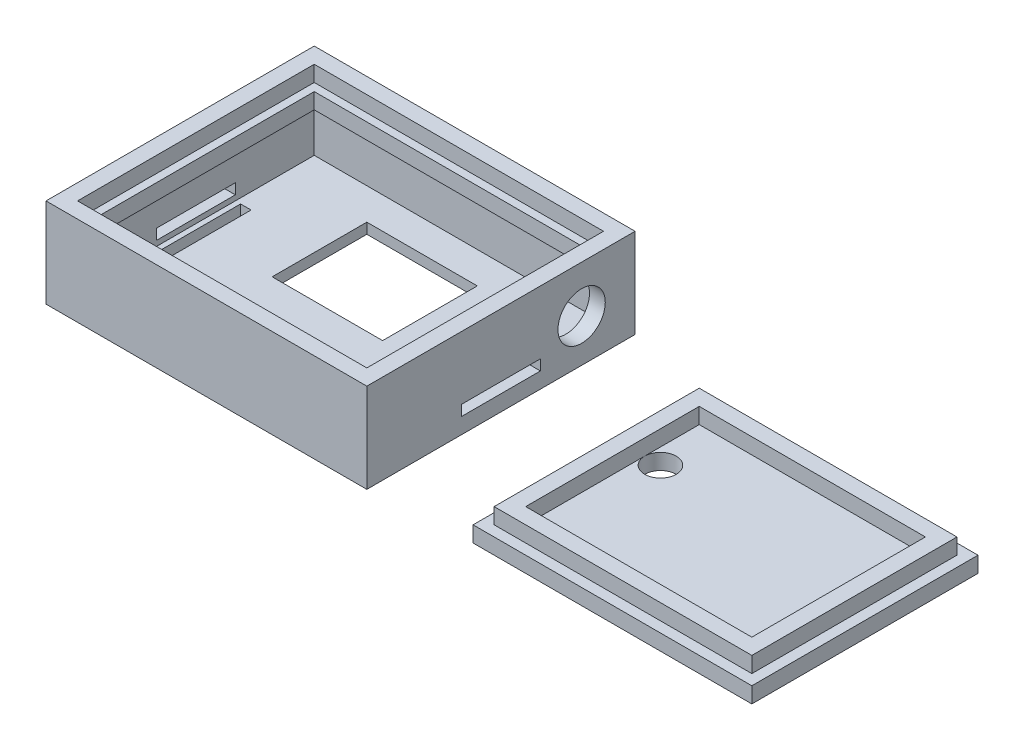
SolidWorks part; units mm, degrees
ref_plane "Front Plane" through (0, 0, 0) normal (0, 0, 1) x (1, 0, 0)
ref_plane "Top Plane" through (0, 0, 0) normal (0, 1, 0) x (1, 0, 0)
ref_plane "Right Plane" through (0, 0, 0) normal (1, 0, 0) x (0, 0, -1)
sketch "Sketch1" plane through (0, 0, 0) normal (0, 1, 0) x (1, 0, 0)
  line L1 (1.0668, -0.2667) -> (62.0668, -0.2667)
  line L2 (1.0668, -0.2667) -> (1.0668, 50.7333)
  line L3 (1.0668, 50.7333) -> (62.0668, 50.7333)
  line L4 (62.0668, -0.2667) -> (62.0668, 50.7333)
  dimension "D1" = 61
  dimension "D2" = 51
extrude "Boss-Extrude1" add sketch "Sketch1" along normal blind 18
sketch "Sketch2" plane through (0, 18, 0) normal (0, 1, 0) x (1, 0, 0)
  line L8 (4.0668, 47.7333) -> (4.0668, 2.7333)
  line L9 (4.0668, 2.7333) -> (59.0668, 2.7333)
  line L10 (59.0668, 2.7333) -> (59.0668, 47.7333)
  line L11 (59.0668, 47.7333) -> (4.0668, 47.7333)
  line L12 (4.0668, 47.7333) -> (4.0668, 2.7333)
  line L13 (4.0668, 2.7333) -> (59.0668, 2.7333)
  line L14 (59.0668, 2.7333) -> (59.0668, 47.7333)
  line L15 (59.0668, 47.7333) -> (4.0668, 47.7333)
  dimension "D1" = 3
extrude "Cut-Extrude1" cut sketch "Sketch2" against normal blind 15 contours L12 L13 L14 L15
sketch "Sketch4" plane through (59.0668, 0, 0) normal (-1, 0, 0) x (0, 0, 1)
  line L0 (-47.7333, 18) -> (-47.7333, 12)
  line L1 (-47.7333, 3) -> (-47.7333, 18) construction
  line L2 (-2.7333, 18) -> (-2.7333, 15)
  line L3 (-2.7333, 3) -> (-2.7333, 18) construction
  line L5 (-2.7333, 15) -> (-47.7333, 15)
  line L6 (-2.7333, 15) -> (-2.7333, 12)
  line L7 (-2.7333, 12) -> (-47.7333, 12)
  line L8 (-47.7333, 15) -> (-47.7333, 12)
  line M5 (-2.7333, 3) -> (-2.7333, 18)
extrude "Boss-Extrude3" add sketch "Sketch4" along normal blind 55 contours L7 L5 L0 M5
sketch "Sketch5" plane through (0, 15, 0) normal (0, 1, 0) x (1, 0, 0)
  line L8 (56.0668, 5.7333) -> (56.0668, 44.7333)
  line L9 (56.0668, 44.7333) -> (7.0668, 44.7333)
  line L10 (7.0668, 44.7333) -> (7.0668, 5.7333)
  line L11 (7.0668, 5.7333) -> (56.0668, 5.7333)
  line L12 (56.0668, 5.7333) -> (56.0668, 44.7333)
  line L13 (56.0668, 44.7333) -> (7.0668, 44.7333)
  line L14 (7.0668, 44.7333) -> (7.0668, 5.7333)
  line L15 (7.0668, 5.7333) -> (56.0668, 5.7333)
  dimension "D1" = 3
extrude "Cut-Extrude2" cut sketch "Sketch5" against normal blind 3
sketch "Sketch6" plane through (0, 3, 0) normal (0, 1, 0) x (1, 0, 0)
  line L0 (4.0668, 47.7333) -> (20.0668, 47.7333)
  line L1 (59.0668, 47.7333) -> (4.0668, 47.7333) construction
  line L2 (20.0668, 47.7333) -> (20.0668, 41.7333)
  line L3 (20.0668, 47.7333) -> (41.0668, 47.7333)
  line L5 (41.0668, 47.7333) -> (41.0668, 23.7333)
  line L7 (20.0668, 41.7333) -> (41.0668, 41.7333)
  line L8 (20.0668, 41.7333) -> (20.0668, 23.7333)
  line L9 (20.0668, 23.7333) -> (41.0668, 23.7333)
  line L10 (41.0668, 41.7333) -> (41.0668, 23.7333)
extrude "Cut-Extrude3" cut sketch "Sketch6" against normal blind 3 contours L8 L9 L5 L7
sketch "Sketch7" plane through (1.0668, 0, 0) normal (-1, 0, 0) x (0, 0, 1)
  line L0 (-50.7333, 0) -> (-50.7333, 4)
  line L1 (-50.7333, 18) -> (-50.7333, 0) construction
  line L2 (-50.7333, 4) -> (-32.7333, 4)
  line L3 (0.2667, 0) -> (0.2667, 6)
  line L5 (0.2667, 18) -> (0.2667, 0) construction
  line L7 (0.2667, 6) -> (-17.7333, 6)
  line L9 (-17.7333, 6) -> (-32.7333, 6)
  line L10 (-17.7333, 6) -> (-17.7333, 4)
  line L11 (-17.7333, 4) -> (-32.7333, 4)
  line L12 (-32.7333, 6) -> (-32.7333, 4)
extrude "Cut-Extrude5" cut sketch "Sketch7" against normal blind 61 contours L9 L12 L11 L10
sketch "Sketch8" plane through (0, 0, 0) normal (0, -1, 0) x (-1, 0, 0)
  line L0 (-1.0668, 50.7333) -> (-1.0668, 32.7333)
  line L1 (-1.0668, 50.7333) -> (-1.0668, -0.2667) construction
  line L2 (-1.0668, 32.7333) -> (-5.0668, 32.7333)
  line L3 (-1.0668, -0.2667) -> (-1.0668, 17.7333)
  line L4 (-1.0668, 17.7333) -> (-7.0668, 17.7333)
  line L6 (-7.0668, 17.7333) -> (-5.0668, 17.7333)
  line L7 (-7.0668, 17.7333) -> (-7.0668, 32.7333)
  line L8 (-7.0668, 32.7333) -> (-5.0668, 32.7333)
  line L9 (-5.0668, 17.7333) -> (-5.0668, 32.7333)
extrude "Cut-Extrude6" cut sketch "Sketch8" against normal blind 3 contours L4 L9 L8 L7
sketch "Sketch9" plane through (0, 0, 0) normal (0, -1, 0) x (-1, 0, 0)
  line L0 (-62.0668, -0.2667) -> (-62.0668, 17.7333)
  line L1 (-62.0668, -0.2667) -> (-62.0668, 50.7333) construction
  line L2 (-62.0668, 17.7333) -> (-58.0668, 17.7333)
  line L3 (-62.0668, 50.7333) -> (-62.0668, 32.7333)
  line L4 (-62.0668, 32.7333) -> (-56.0668, 32.7333)
  line L6 (-58.0668, 17.7333) -> (-56.0668, 17.7333)
  line L7 (-58.0668, 17.7333) -> (-58.0668, 32.7333)
  line L8 (-58.0668, 32.7333) -> (-56.0668, 32.7333)
  line L9 (-56.0668, 17.7333) -> (-56.0668, 32.7333)
extrude "Cut-Extrude7" cut sketch "Sketch9" against normal blind 3 contours L6 L9 L4 L7
sketch "Sketch10" plane through (62.0668, 0, 0) normal (1, 0, 0) x (0, 0, -1)
  line L0 (50.7333, 0) -> (50.7333, 3.4631)
  line L1 (50.7333, 18) -> (50.7333, 0) construction
  circle A0 centre (40.5681, 9.1318) radius 4.5
extrude "Cut-Extrude8" cut sketch "Sketch10" against normal blind 6 contours A0
sketch "Sketch11" plane through (0, 0, 0) normal (0, -1, 0) x (-1, 0, 0)
  line L5 (-80, 0) -> (-135, 0)
  line L6 (-80, 0) -> (-80, 45)
  line L7 (-80, 45) -> (-135, 45)
  line L8 (-135, 0) -> (-135, 45)
extrude "Boss-Extrude4" add sketch "Sketch11" against normal blind 3 separate body
sketch "Sketch12" plane through (0, 3, 0) normal (0, 1, 0) x (1, 0, 0)
  line L8 (83, 42) -> (83, 3)
  line L9 (83, 3) -> (132, 3)
  line L10 (132, 3) -> (132, 42)
  line L11 (132, 42) -> (83, 42)
  line L12 (83, 42) -> (83, 3)
  line L13 (83, 3) -> (132, 3)
  line L14 (132, 3) -> (132, 42)
  line L15 (132, 42) -> (83, 42)
  dimension "D1" = 3
extrude "Boss-Extrude5" add sketch "Sketch12" along normal blind 3 contours L12 L13 L14 L15
sketch "Sketch13" plane through (0, 6, 0) normal (0, 1, 0) x (1, 0, 0)
  line L8 (129, 39) -> (86, 39)
  line L9 (86, 39) -> (86, 6)
  line L10 (86, 6) -> (129, 6)
  line L11 (129, 6) -> (129, 39)
  line L12 (129, 39) -> (86, 39)
  line L13 (86, 39) -> (86, 6)
  line L14 (86, 6) -> (129, 6)
  line L15 (129, 6) -> (129, 39)
  dimension "D1" = 3
extrude "Cut-Extrude9" cut sketch "Sketch13" against normal blind 3
sketch "Sketch15" plane through (0, 3, 0) normal (0, 1, 0) x (1, 0, 0)
  line L0 (86, 6) -> (86, 13)
  line L1 (86, 39) -> (86, 6) construction
  line L2 (86, 13) -> (92, 13)
  line L3 (92, 13) -> (92, 19)
  line L4 (92, 19) -> (86, 13)
  circle A0 centre (89, 16) radius 3
extrude "Cut-Extrude11" cut sketch "Sketch15" against normal blind 3 contours L4 A0 | A0 L4
sketch "Sketch20" plane through (0, 0, 0.2667) normal (0, 0, 1) x (1, 0, 0)
  line L1 (1.0668, 0) -> (1.0668, 1)
  line L2 (1.0668, 18) -> (1.0668, 0) construction
  line L4 (1.0668, 1) -> (62.0668, 1)
  line L5 (1.0668, 1) -> (1.0668, 0)
  line L6 (1.0668, 0) -> (62.0668, 0)
  line L7 (62.0668, 1) -> (62.0668, 0)
  line M1 (1.0668, 0) -> (62.0668, 0)
  line M2 (62.0668, 0) -> (62.0668, 18)
  line M4 (1.0668, 18) -> (1.0668, 0)
extrude "Cut-Extrude12" cut sketch "Sketch20" against normal blind 51 contours L4 M4 M1 M2
move or copy body "Body-Move/Copy1" bodies to move or copy 117 copy no translate (0, -1, 0)
sketch "Sketch23" plane through (0, 3, 0) normal (0, 1, 0) x (1, 0, 0)
  line L0 (86, 39) -> (86, 28.6255)
  line L1 (86, 39) -> (86, 16) construction
  line L2 (86, 28.6255) -> (89, 28.6255)
  circle A0 centre (89, 28.6255) radius 3
extrude "Cut-Extrude13" cut sketch "Sketch23" against normal blind 10
sketch "Sketch24" plane through (0, 0, 0) normal (0, 0, 1) x (1, 0, 0)
  line L1 (80, 3) -> (135, 3)
  line L2 (80, 3) -> (80, 0)
  line L3 (80, 0) -> (135, 0)
  line L4 (135, 3) -> (135, 0)
extrude "Boss-Extrude6" add sketch "Sketch24" against normal blind 25
sketch "Sketch25" plane through (80, 0, 0) normal (-1, 0, 0) x (0, 0, 1)
  line L1 (-45, 3) -> (0, 3)
  line L2 (-45, 3) -> (-45, 0)
  line L3 (-45, 0) -> (0, 0)
  line L4 (0, 3) -> (0, 0)
extrude "Cut-Extrude15" cut sketch "Sketch25" against normal blind 1
sketch "Sketch26" plane through (135, 0, 0) normal (1, 0, 0) x (0, 0, -1)
  line L1 (0, 3) -> (45, 3)
  line L2 (0, 3) -> (0, 0)
  line L3 (0, 0) -> (45, 0)
  line L4 (45, 3) -> (45, 0)
extrude "Cut-Extrude16" cut sketch "Sketch26" against normal blind 1
sketch "Sketch27" plane through (0, 0, -45) normal (0, 0, -1) x (-1, 0, 0)
  line L1 (-134, 3) -> (-81, 3)
  line L2 (-134, 3) -> (-134, 0)
  line L3 (-134, 0) -> (-81, 0)
  line L4 (-81, 3) -> (-81, 0)
extrude "Cut-Extrude17" cut sketch "Sketch27" against normal blind 1
sketch "Sketch28" plane through (0, 0, 0) normal (0, 0, 1) x (1, 0, 0)
  line L1 (81, 3) -> (134, 3)
  line L2 (81, 3) -> (81, 0)
  line L3 (81, 0) -> (134, 0)
  line L4 (134, 3) -> (134, 0)
extrude "Cut-Extrude18" cut sketch "Sketch28" against normal blind 1
sketch "Sketch30" plane through (7.0668, 0, 0) normal (1, 0, 0) x (0, 0, -1)
  line L1 (5.7333, 14) -> (44.7333, 14)
  line L2 (5.7333, 14) -> (5.7333, 11)
  line L3 (5.7333, 11) -> (44.7333, 11)
  line L4 (44.7333, 14) -> (44.7333, 11)
extrude "Cut-Extrude23" cut sketch "Sketch30" against normal blind 1.5
sketch "Sketch35" plane through (56.0668, 0, 0) normal (-1, 0, 0) x (0, 0, 1)
  line L1 (-44.7333, 14) -> (-5.7333, 14)
  line L2 (-44.7333, 14) -> (-44.7333, 11)
  line L3 (-44.7333, 11) -> (-5.7333, 11)
  line L4 (-5.7333, 14) -> (-5.7333, 11)
extrude "Cut-Extrude24" cut sketch "Sketch35" against normal blind 1.5
sketch "Sketch36" plane through (0, 0, -5.7333) normal (0, 0, -1) x (-1, 0, 0)
  line L1 (-57.5668, 14) -> (-5.5668, 14)
  line L2 (-57.5668, 14) -> (-57.5668, 11)
  line L3 (-57.5668, 11) -> (-5.5668, 11)
  line L4 (-5.5668, 14) -> (-5.5668, 11)
extrude "Cut-Extrude25" cut sketch "Sketch36" against normal blind 1.5
sketch "Sketch38" plane through (0, 0, -44.7333) normal (0, 0, 1) x (1, 0, 0)
  line L1 (5.5668, 14) -> (57.5668, 14)
  line L2 (5.5668, 14) -> (5.5668, 11)
  line L3 (5.5668, 11) -> (57.5668, 11)
  line L4 (57.5668, 14) -> (57.5668, 11)
extrude "Cut-Extrude26" cut sketch "Sketch38" against normal blind 1.5
